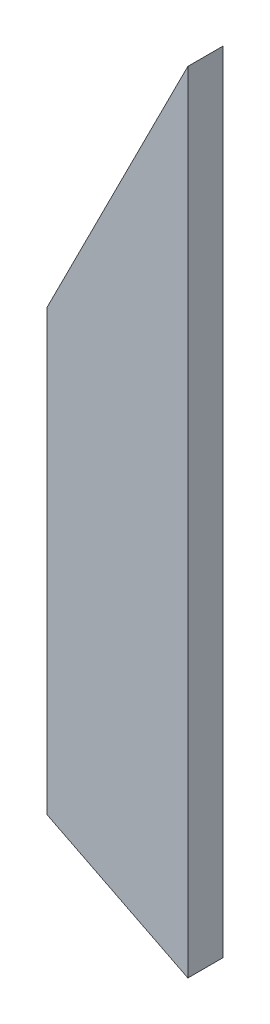
SolidWorks part; units mm, degrees
ref_plane "Front Plane" through (0, 0, 0) normal (0, 0, 1) x (1, 0, 0)
ref_plane "Top Plane" through (0, 0, 0) normal (0, 1, 0) x (1, 0, 0)
ref_plane "Right Plane" through (0, 0, 0) normal (1, 0, 0) x (0, 0, -1)
sketch "Sketch1" plane through (0, 0, 0) normal (0, 0, 1) x (1, 0, 0)
  line L0 (25.4, 142.24) -> (-25.4, 41.5534)
  line L1 (-25.4, 142.24) -> (25.4, 142.24)
  line L2 (-25.4, 142.24) -> (-25.4, -142.24)
  line L3 (-25.4, -142.24) -> (25.4, -142.24)
  line L4 (25.4, 142.24) -> (25.4, -142.24)
  line L5 (-25.4, 142.24) -> (25.4, -142.24) construction
  line L6 (-25.4, -142.24) -> (25.4, 142.24) construction
  line L7 (25.4, -142.24) -> (-25.4, -116.6175)
  point P0 (0, 0)
  dimension "D1" = 284.48
  dimension "D2" = 50.8
  dimension "D3" = 112.776
  dimension "D4" = 56.896
extrude "Boss-Extrude1" add sketch "Sketch1" along normal blind 12.7
